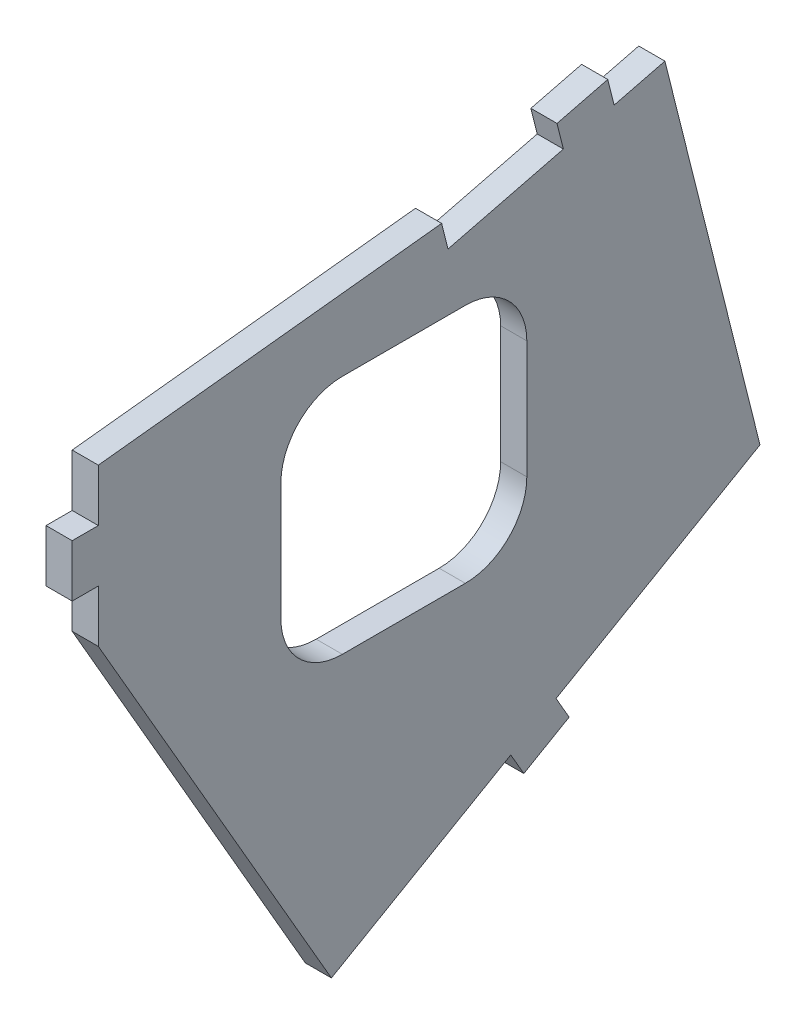
SolidWorks part; units mm, degrees
ref_plane "Plan de face" through (0, 0, 0) normal (0, 0, 1) x (1, 0, 0)
ref_plane "Plan de dessus" through (0, 0, 0) normal (0, 1, 0) x (1, 0, 0)
ref_plane "Plan de droite" through (0, 0, 0) normal (1, 0, 0) x (0, 0, -1)
sketch "Esquisse1" plane through (0, 0, 0) normal (1, 0, 0) x (0, 0, -1)
  line L0 (-11.75, 11.25) -> (-11.75, -11.25) construction
  line L1 (20.4282, -55.7414) -> (-13.8434, -75.5282)
  line L2 (68.0596, -28.2414) -> (49.8899, 44.3583)
  line L4 (-13.8434, -75.5282) -> (-58.3876, 1.6246)
  line L5 (-75, -75) -> (75, 75) construction
  line L6 (-75, 75) -> (75, -75) construction
  line L7 (-23.5, 23) -> (23.5, 23) construction
  line L8 (-23.5, 23) -> (-23.5, -23) construction
  line L9 (-23.5, -23) -> (23.5, -23) construction
  line L10 (23.5, 23) -> (23.5, -23) construction
  line L11 (-23.5, 23) -> (23.5, -23) construction
  line L12 (-23.5, -23) -> (23.5, 23) construction
  line L13 (0, 23) -> (0, -23) construction
  line L14 (-11.75, 23) -> (11.75, 23)
  line L15 (23.5, 11.25) -> (23.5, -11.25)
  line L16 (11.75, -23) -> (-11.75, -23)
  line L17 (-23.5, -11.25) -> (-23.5, 11.25)
  line L18 (68.0596, -28.2414) -> (29.0885, -50.7414)
  line L22 (7.2245, 38.8345) -> (8.4384, 33.9841)
  line L23 (8.4384, 33.9841) -> (30.4883, 39.5026)
  line L24 (-58.3876, 11.6246) -> (-63.3876, 11.6246)
  line L25 (40.1891, 41.9304) -> (49.8899, 44.3583)
  line L26 (-58.3876, 11.6246) -> (-58.3876, 1.6246)
  line L27 (7.2245, 38.8345) -> (-58.3876, 31.6246)
  line L28 (-58.3876, 31.6246) -> (-58.3876, 21.6246)
  line L32 (-58.3876, 21.6246) -> (-63.3876, 21.6246)
  line L33 (-63.3876, 11.6246) -> (-63.3876, 21.6246)
  line L34 (20.4282, -55.7414) -> (22.9282, -60.0715)
  line L35 (29.0885, -50.7414) -> (31.5885, -55.0715)
  line L36 (22.9282, -60.0715) -> (31.5885, -55.0715)
  line L38 (40.1891, 41.9304) -> (38.9752, 46.7808)
  line L39 (30.4883, 39.5026) -> (29.2744, 44.353)
  line L40 (38.9752, 46.7808) -> (29.2744, 44.353)
  arc A0 (-11.75, 23) -> (-23.5, 11.25) centre (-11.75, 11.25) ccw
  arc A1 (-11.75, -23) -> (-23.5, -11.25) centre (-11.75, -11.25) cw
  arc A2 (11.75, -23) -> (23.5, -11.25) centre (11.75, -11.25) ccw
  arc A3 (11.75, 23) -> (23.5, 11.25) centre (11.75, 11.25) cw
  point P0 (0, 0)
  point P6 (0, 0)
  dimension "D1" = 46
  dimension "D2" = 47
  dimension "D3" = 94.5735
  dimension "D4" = 150
  dimension "D5" = 11.75
  dimension "D6" = 7.2245
  dimension "D7" = 8.4384
  dimension "D8" = 10
  dimension "D9" = 49.8899
  dimension "D10" = 68.0596
  dimension "D11" = 31.6246
  dimension "D12" = 13.8434
  dimension "D13" = 58.3876
  dimension "D14" = 1.6246
  dimension "D15" = 33.9841
  dimension "D17" = 5
  dimension "D18" = 10
  dimension "D20" = 45
  dimension "D21" = 10
  dimension "D22" = 10
extrude "Boss.-Extru.1" add sketch "Esquisse1" along normal blind 5
